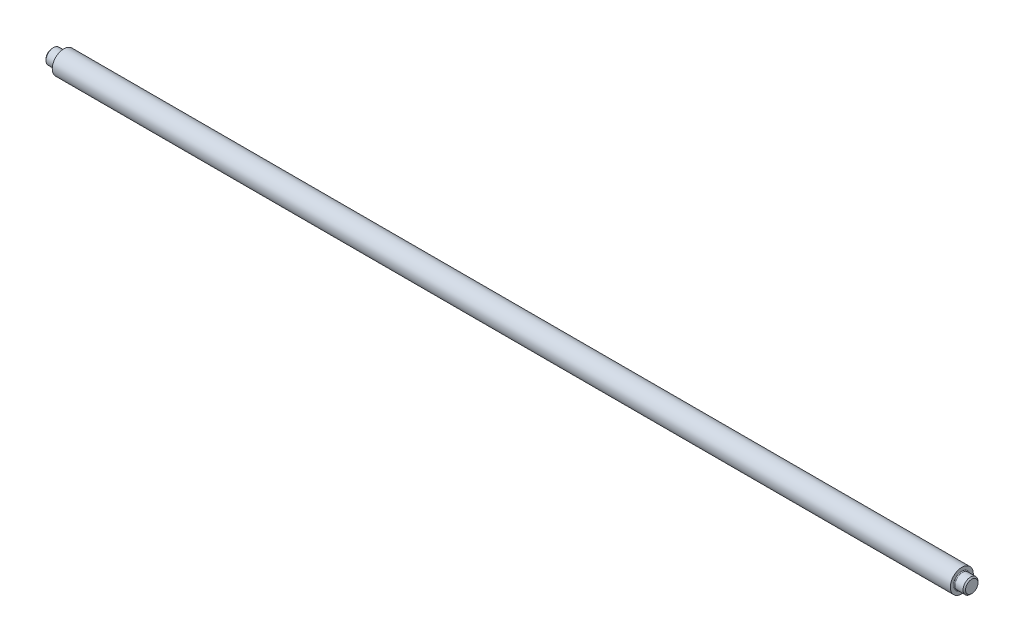
SolidWorks part; units mm, degrees
ref_plane "Front Plane" through (0, 0, 0) normal (0, 0, 1) x (1, 0, 0)
ref_plane "Top Plane" through (0, 0, 0) normal (0, 1, 0) x (1, 0, 0)
ref_plane "Right Plane" through (0, 0, 0) normal (1, 0, 0) x (0, 0, -1)
ref_plane "Plane1" through (0, 0, 0) normal (0, 0, 1) x (1, 0, 0)
sketch "Sketch1" plane through (0, 0, 0) normal (0, 0, 1) x (1, 0, 0)
  line L0 (4.6154, 0) -> (4.6154, 4.6154)
  line L1 (4.6154, 4.6154) -> (364.6154, 4.6154)
  line L2 (364.6154, 4.6154) -> (364.6154, 0)
  line L3 (364.6154, 0) -> (4.6154, 0)
  line L4 (364.6154, 0) -> (4.6154, 0) construction
  dimension "D1" = 360
revolve "Revolve1" add sketch "Sketch1" angle 360 about L4
cosmetic thread "Cosmetic Thread1" parameters "D1"=360, "D2"=6.2
ref_plane "Plane2" through (0, 0, 0) normal (0, 0, 1) x (1, 0, 0)
sketch "Sketch2" plane through (0, 0, 0) normal (0, 0, 1) x (1, 0, 0)
  line L0 (0, 0) -> (0, 2.5)
  line L1 (0, 2.5) -> (0.5, 3)
  line L2 (0.5, 3) -> (3.7, 3)
  line L3 (4, 3.3) -> (4, 0)
  line L4 (4, 0) -> (0, 0)
  line L5 (4, 0) -> (0, 0) construction
  arc A0 (3.7, 3) -> (4, 3.3) centre (3.7, 3.3) ccw
revolve "Revolve2" add sketch "Sketch2" angle 360 about L5
ref_plane "Plane3" through (0, 0, 0) normal (0, 0, 1) x (1, 0, 0)
sketch "Sketch3" plane through (0, 0, 0) normal (0, 0, 1) x (1, 0, 0)
  line L0 (364.6154, 0) -> (364.6154, 3.3)
  line L1 (364.9154, 3) -> (368.1154, 3)
  line L2 (368.1154, 3) -> (368.6154, 2.5)
  line L3 (368.6154, 2.5) -> (368.6154, 0)
  line L4 (368.6154, 0) -> (364.6154, 0)
  line L5 (368.6154, 0) -> (364.6154, 0) construction
  arc A0 (364.6154, 3.3) -> (364.9154, 3) centre (364.9154, 3.3) ccw
revolve "Revolve3" add sketch "Sketch3" angle 360 about L5
